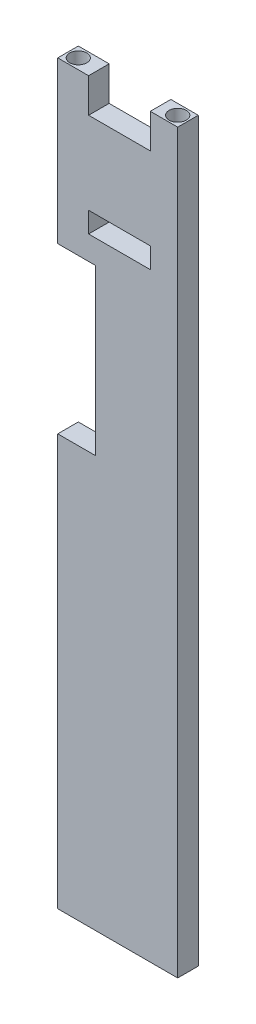
SolidWorks part; units mm, degrees
material "Plywood"
ref_plane "Plan de face" through (0, 0, 0) normal (0, 0, 1) x (1, 0, 0)
ref_plane "Plan de dessus" through (0, 0, 0) normal (0, 1, 0) x (1, 0, 0)
ref_plane "Plan de droite" through (0, 0, 0) normal (1, 0, 0) x (0, 0, -1)
sketch "Esquisse1" plane through (0, 0, 0) normal (0, 0, 1) x (1, 0, 0)
  line L1 (0, 0) -> (35, 0)
  line L2 (0, 0) -> (0, 215)
  line L3 (0, 215) -> (35, 215)
  line L4 (35, 0) -> (35, 215)
  dimension "D1" = 35
  dimension "D2" = 215
extrude "Boss.-Extru.1" add sketch "Esquisse1" along normal blind 6
sketch "Esquisse2" plane through (0, 215, 0) normal (0, 1, 0) x (1, 0, 0)
  line L0 (35, 0) -> (0, 0) construction
  line L1 (9, 0) -> (27, 0)
  line L2 (9, 0) -> (9, -6)
  line L3 (9, -6) -> (27, -6)
  line L4 (27, 0) -> (27, -6)
  line L5 (35, -6) -> (0, -6) construction
  line L6 (0, -6) -> (0, 0) construction
  dimension "D1" = 9
  dimension "D2" = 18
extrude "Enlèv. mat.-Extru.1" cut sketch "Esquisse2" against normal blind 10
sketch "Esquisse3" plane through (0, 0, 6) normal (0, 0, 1) x (1, 0, 0)
  line L0 (35, 215) -> (27, 215) construction
  line L1 (27, 175) -> (9, 175)
  line L2 (27, 175) -> (27, 181)
  line L3 (27, 181) -> (9, 181)
  line L4 (9, 175) -> (9, 181)
  line L5 (0, 215) -> (0, 0) construction
  dimension "D1" = 34
  dimension "D2" = 6
  dimension "D3" = 9
  dimension "D4" = 18
extrude "Enlèv. mat.-Extru.2" cut sketch "Esquisse3" against normal through all
sketch "Esquisse4" plane through (0, 0, 0) normal (0, 0, -1) x (-1, 0, 0)
  line L0 (0, 215) -> (0, 0) construction
  line L1 (0, 168.0546) -> (-11, 168.0546)
  line L2 (0, 168.0546) -> (0, 120)
  line L3 (0, 120) -> (-11, 120)
  line L4 (-11, 168.0546) -> (-11, 120)
  dimension "D1" = 11
extrude "Enlèv. mat.-Extru.3" cut sketch "Esquisse4" against normal through all
sketch "Esquisse5" plane through (0, 215, 0) normal (0, 1, 0) x (1, 0, 0)
  line L0 (0, -6) -> (0, 0) construction
  line L3 (9, 0) -> (0, 0) construction
  circle A0 centre (3, -3) radius 2.5
  dimension "D1" = 5
  dimension "D2" = 3
  dimension "D3" = 3
extrude "Enlèv. mat.-Extru.4" cut sketch "Esquisse5" against normal blind 10
pattern_linear "Répétition linéaire1" count 2 spacing 29 along (1, 0, 0) of "Enlèv. mat.-Extru.4"
